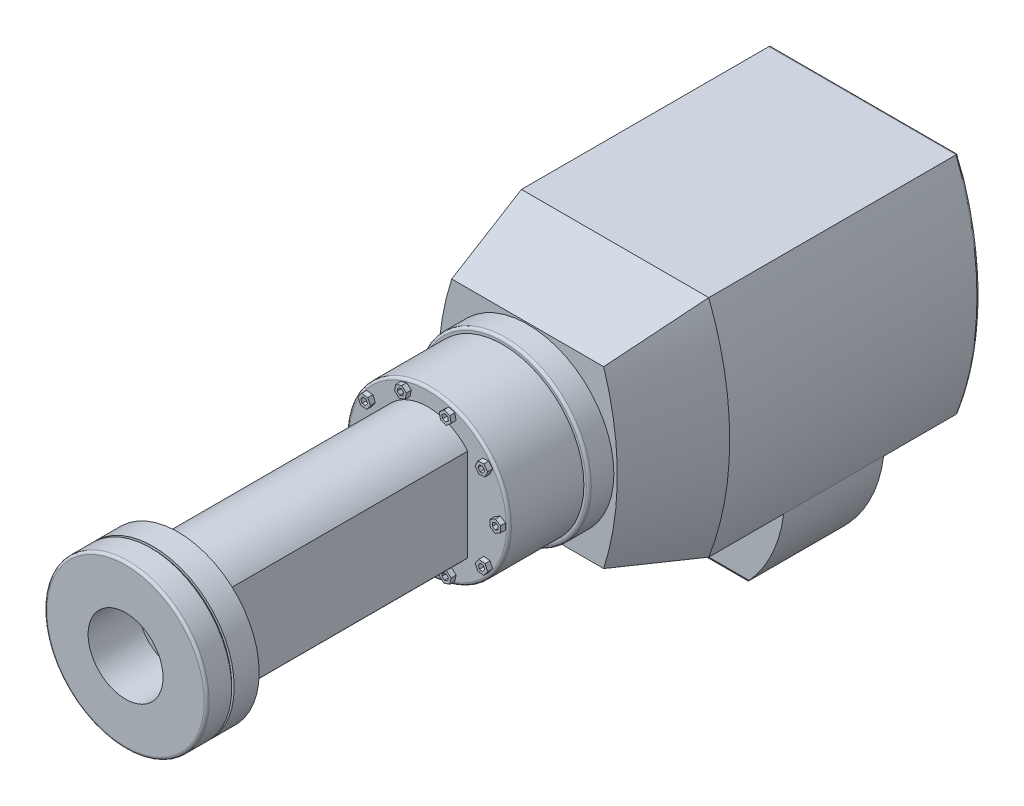
SolidWorks part; units mm, degrees
ref_plane "Front Plane" through (0, 0, 0) normal (0, 0, 1) x (1, 0, 0)
ref_plane "Top Plane" through (0, 0, 0) normal (0, 1, 0) x (1, 0, 0)
ref_plane "Right Plane" through (0, 0, 0) normal (1, 0, 0) x (0, 0, -1)
sketch "Sketch1" plane through (0, 0, 0) normal (0, 0, 1) x (1, 0, 0)
  line L0 (0, 45) -> (0, -45) construction
  line L1 (-37.5, 45) -> (37.5, 45)
  line L2 (-37.5, -45) -> (37.5, -45)
  arc A0 (-37.5, 45) -> (-37.5, -45) centre (79.119, 0) ccw
  arc A1 (37.5, 45) -> (37.5, -45) centre (-79.119, 0) cw
  point P4 (0, 0)
  point P8 (0, 45)
  point P11 (0, -45)
  dimension "D1" = 90
  dimension "D2" = 75
extrude "Boss-Extrude1" add sketch "Sketch1" along normal blind 100
sketch "Sketch2" plane through (0, 0, 100) normal (0, 0, 1) x (1, 0, 0)
  line L2 (37.5, 45) -> (-37.5, 45)
  line L3 (-37.5, -45) -> (37.5, -45)
  line L4 (37.5, 45) -> (-37.5, 45)
  line L5 (-37.5, -45) -> (37.5, -45)
  arc A2 (37.5, -45) -> (37.5, 45) centre (-79.119, 0) ccw
  arc A3 (-37.5, 45) -> (-37.5, -45) centre (79.119, 0) ccw
  arc A4 (37.5, -45) -> (37.5, 45) centre (-79.119, 0) ccw
  arc A5 (-37.5, 45) -> (-37.5, -45) centre (79.119, 0) ccw
  dimension "D1" = 0
ref_plane "Plane1" through (0, 0, 135) normal (0, 0, 1) x (1, 0, 0)
sketch "Sketch3" plane through (0, 0, 135) normal (0, 0, 1) x (1, 0, 0)
  line L4 (30.4255, 35) -> (-30.4255, 35)
  line L5 (-30.4255, -35) -> (30.4255, -35)
  line L6 (30.4255, 35) -> (-30.4255, 35)
  line L7 (-30.4255, -35) -> (30.4255, -35)
  arc A4 (-30.4255, 35) -> (-30.4255, -35) centre (79.119, 0) ccw
  arc A5 (30.4255, -35) -> (30.4255, 35) centre (-79.119, 0) ccw
  arc A6 (-30.4255, 35) -> (-30.4255, -35) centre (79.119, 0) ccw
  arc A7 (30.4255, -35) -> (30.4255, 35) centre (-79.119, 0) ccw
  dimension "D1" = 10
loft "Loft1" add profiles "Sketch3", "Sketch2"
sketch "Sketch4" plane through (0, 0, 135) normal (0, 0, 1) x (1, 0, 0)
  circle A0 centre (0, 0) radius 34.5
  dimension "D1" = 69
extrude "Boss-Extrude2" add sketch "Sketch4" along normal blind 10
sketch "Sketch5" plane through (0, 0, 145) normal (0, 0, 1) x (1, 0, 0)
  circle A2 centre (0, 0) radius 32.5
  circle A3 centre (0, 0) radius 32.5
  dimension "D1" = 2
extrude "Boss-Extrude3" add sketch "Sketch5" along normal blind 30
sketch "Sketch6" plane through (0, 0, 175) normal (0, 0, 1) x (1, 0, 0)
  line L0 (0, 0) -> (29, 0) construction
  line L1 (30.1651, 0.6726) -> (29, 1.3453)
  line L2 (29, 2.5) -> (26.8349, 1.25)
  line L3 (26.8349, 1.25) -> (26.8349, -1.25)
  line L4 (26.8349, -1.25) -> (29, -2.5)
  line L5 (29, -2.5) -> (31.1651, -1.25)
  line L6 (31.1651, -1.25) -> (31.1651, 1.25)
  line L7 (31.1651, 1.25) -> (29, 2.5)
  line L8 (29, 1.3453) -> (27.8349, 0.6726)
  line L9 (27.8349, 0.6726) -> (27.8349, -0.6726)
  line L10 (27.8349, -0.6726) -> (29, -1.3453)
  line L11 (29, -1.3453) -> (30.1651, -0.6726)
  line L12 (30.1651, -0.6726) -> (30.1651, 0.6726)
  circle A0 centre (29, 0) radius 2.1651 construction
  dimension "D1" = 29
  dimension "D2" = 5
  dimension "D3" = 1
extrude "Boss-Extrude5" add sketch "Sketch6" along normal blind 2
pattern_circular "CirPattern1" count 10 over 360 about axis through (0, 0, 0) along (0, 0, 1) of "Boss-Extrude5"
sketch "Sketch7" plane through (0, 0, 175) normal (0, 0, 1) x (1, 0, 0)
  line L0 (0, 0) -> (16, 0) construction
  line L1 (0, 13.5942) -> (0, -13.5942) construction
  line L2 (16, 18.5) -> (16, -18.5)
  line L3 (-16, 18.5) -> (-16, -18.5)
  arc A0 (-16, 18.5) -> (16, 18.5) centre (0, 4.8985) cw
  arc A1 (-16, -18.5) -> (16, -18.5) centre (0, -4.8985) ccw
  point P5 (0, 0)
  point P9 (16, 0)
  dimension "D1" = 16
  dimension "D2" = 37
extrude "Boss-Extrude6" add sketch "Sketch7" along normal blind 100
sketch "Sketch8" plane through (0, 0, 275) normal (0, 0, 1) x (1, 0, 0)
  line L2 (-16, 18.5) -> (-16, -18.5)
  line L3 (16, -18.5) -> (16, 18.5)
  line L4 (-16, 18.5) -> (-16, -18.5)
  line L5 (16, -18.5) -> (16, 18.5)
  circle A0 centre (0, 0) radius 32.5 construction
  circle A1 centre (0, 0) radius 32.5
  arc A2 (16, 18.5) -> (-16, 18.5) centre (0, 4.8985) ccw
  arc A3 (-16, -18.5) -> (16, -18.5) centre (0, -4.8985) ccw
  arc A4 (16, 18.5) -> (-16, 18.5) centre (0, 4.8985) ccw
  arc A5 (-16, -18.5) -> (16, -18.5) centre (0, -4.8985) ccw
  dimension "D1" = 0
extrude "Boss-Extrude7" add sketch "Sketch8" along normal blind 10 contours A1
sketch "Sketch9" plane through (0, 0, 285) normal (0, 0, 1) x (1, 0, 0)
  circle A2 centre (0, 0) radius 31.5
  circle A3 centre (0, 0) radius 31.5
  dimension "D1" = 1
extrude "Boss-Extrude8" add sketch "Sketch9" along normal blind 1
sketch "Sketch10" plane through (0, 0, 286) normal (0, 0, 1) x (1, 0, 0)
  circle A0 centre (0, 0) radius 32.5 construction
  circle A1 centre (0, 0) radius 32.5
extrude "Boss-Extrude9" add sketch "Sketch10" along normal blind 10
ref_plane "Plane2" through (-37.5, 0, 0) normal (1, 0, 0) x (0, 0, -1)
sketch "Sketch11" plane through (-37.5, 0, 0) normal (1, 0, 0) x (0, 0, -1)
  line L0 (-100, -45) -> (0, -45) construction
  circle A0 centre (-50, -45) radius 42.5
  dimension "D1" = 85
extrude "Boss-Extrude10" add sketch "Sketch11" along normal mid plane 21
sketch "Sketch12" plane through (-27, 0, 0) normal (1, 0, 0) x (0, 0, -1)
  line L0 (-50, -45) -> (-50, -75) construction
  line L1 (-92.5, -45) -> (-7.5, -45) construction
  line L3 (-70, -45) -> (-70, -75)
  line L4 (-30, -45) -> (-30, -75)
  line L5 (-70, -45) -> (-30, -45)
  arc A1 (-70, -75) -> (-30, -75) centre (-50, -60.3189) ccw
  dimension "D1" = 30
  dimension "D2" = 20
  dimension "D3" = 20
extrude "Boss-Extrude11" add sketch "Sketch12" along normal blind 35
ref_plane "Plane3" through (0, 0, 50) normal (0, 0, 1) x (1, 0, 0)
sketch "Sketch13" plane through (0, 0, 50) normal (0, 0, 1) x (1, 0, 0)
  line L0 (8, -87) -> (8, -45)
  line L1 (8, -45) -> (37.5, -45)
  arc A0 (8, -87) -> (37.5, -45) centre (-17.0578, -38.0398) ccw
  dimension "D1" = 29.5
  dimension "D3" = 55
  dimension "D2" = 42
extrude "Boss-Extrude12" add sketch "Sketch13" along normal mid plane 40
sketch "Sketch14" plane through (8, 0, 0) normal (-1, 0, 0) x (0, 0, 1)
  line L3 (70, -87) -> (70, -75)
  line L4 (30, -75) -> (30, -87)
  line L5 (30, -87) -> (70, -87)
  line L6 (70, -87) -> (70, -75)
  line L7 (30, -75) -> (30, -87)
  line L8 (30, -87) -> (70, -87)
  arc A1 (30, -75) -> (70, -75) centre (50, -60.3189) ccw
  arc A2 (30, -75) -> (70, -75) centre (50, -60.3189) ccw
  dimension "D1" = 0
extrude "Cut-Extrude1" cut sketch "Sketch14" against normal through all
fillet "Fillet1" radius 1 9 edges at (0, 45, 0) (-45.881, 0, 0) (0, -45, 0) (45.881, 0, 0) (32.5, 0, 296) (32.5, 0, 175) (34.5, 0, 145) (-48, -45, 7.5) (-27, -87.5, 50)
sketch "Sketch15" plane through (0, 0, 296) normal (0, 0, 1) x (1, 0, 0)
  circle A0 centre (0, 0) radius 15
extrude "Cut-Extrude2" cut sketch "Sketch15" against normal blind 20
sketch "Sketch16" plane through (-48, 0, 0) normal (-1, 0, 0) x (0, 0, 1)
  circle A0 centre (50, -45) radius 15
  circle A1 centre (50, -45) radius 41.5 construction
extrude "Cut-Extrude4" cut sketch "Sketch16" against normal blind 20
